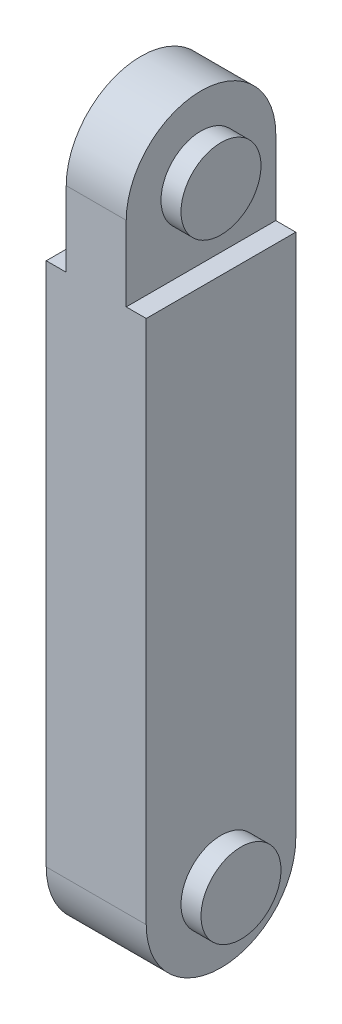
SolidWorks part; units mm, degrees
ref_plane "Front Plane" through (0, 0, 0) normal (0, 0, 1) x (1, 0, 0)
ref_plane "Top Plane" through (0, 0, 0) normal (0, 1, 0) x (1, 0, 0)
ref_plane "Right Plane" through (0, 0, 0) normal (1, 0, 0) x (0, 0, -1)
sketch "Sketch1" plane through (0, 0, 0) normal (1, 0, 0) x (0, 0, -1)
  line L0 (-74.7678, 0) -> (-74.7678, 600)
  line L1 (74.7678, 0) -> (74.7678, 600)
  arc A0 (-74.7678, 600) -> (74.7678, 600) centre (0, 600) cw
  arc A1 (-74.7678, 0) -> (74.7678, 0) centre (0, 0) ccw
extrude "Boss-Extrude1" add sketch "Sketch1" along normal blind 100 contours L0 A0 L1 A1
sketch "Sketch2" plane through (100, 0, 0) normal (1, 0, 0) x (0, 0, -1)
  circle A0 centre (0, 0) radius 40
  circle A1 centre (0, 0) radius 40
sketch "Sketch7" plane through (100, 0, 0) normal (1, 0, 0) x (0, 0, -1)
  line L0 (74.7678, 0) -> (74.7678, 600) construction
  line L1 (-74.7678, 600) -> (-74.7678, 525)
  line L2 (-74.7678, 0) -> (-74.7678, 600) construction
  line L3 (74.7678, 600) -> (74.7678, 525)
  line L4 (74.7678, 525) -> (-74.7678, 525)
  arc A0 (-74.7678, 600) -> (74.7678, 600) centre (0, 600) cw
  dimension "D1" = 75
sketch "Sketch8" plane through (0, 0, 0) normal (-1, 0, 0) x (0, 0, 1)
  line L0 (74.7678, 0) -> (74.7678, 600) construction
  line L1 (-74.7678, 600) -> (-74.7678, 525)
  line L2 (-74.7678, 0) -> (-74.7678, 600) construction
  line L3 (74.7678, 600) -> (74.7678, 525)
  line L4 (74.7678, 525) -> (-74.7678, 525)
  arc A0 (-74.7678, 600) -> (74.7678, 600) centre (0, 600) cw
  dimension "D1" = 75
  dimension "D2" = 75
extrude "Cut-Extrude2" cut sketch "Sketch8" against normal blind 20
extrude "Cut-Extrude3" cut sketch "Sketch7" against normal blind 20 contours L4 L1 A0 L3
sketch "Sketch9" plane through (0, 0, 0) normal (-1, 0, 0) x (0, 0, 1)
  circle A0 centre (0, 0) radius 40
extrude "Boss-Extrude2" add sketch "Sketch9" along normal blind 20
extrude "Boss-Extrude3" add sketch "Sketch2" along normal blind 20 contours A0
sketch "Sketch10" plane through (80, 0, 0) normal (1, 0, 0) x (0, 0, -1)
  circle A0 centre (0, 600) radius 40
sketch "Sketch11" plane through (20, 0, 0) normal (-1, 0, 0) x (0, 0, 1)
  circle A0 centre (0, 600) radius 40
extrude "Boss-Extrude6" add sketch "Sketch10" along normal blind 20 contours A0
extrude "Boss-Extrude7" add sketch "Sketch11" along normal blind 20 contours A0
